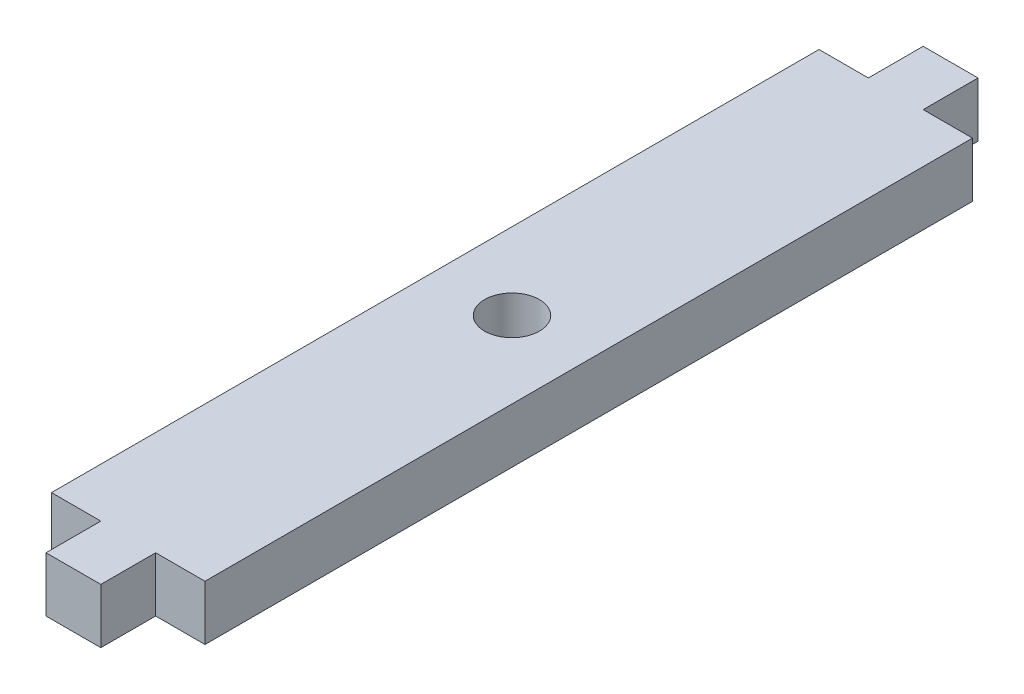
SolidWorks part; units mm, degrees
material "Pine"
ref_plane "Front Plane" through (0, 0, 0) normal (0, 0, 1) x (1, 0, 0)
ref_plane "Top Plane" through (0, 0, 0) normal (0, 1, 0) x (1, 0, 0)
ref_plane "Right Plane" through (0, 0, 0) normal (1, 0, 0) x (0, 0, -1)
sketch "Sketch1" plane through (0, 0, 0) normal (0, 1, 0) x (1, 0, 0)
  line L0 (0, 0) -> (0, 17.78)
  line L1 (0, 17.78) -> (-5.715, 17.78)
  line L2 (-5.715, 17.78) -> (-5.715, 24.13)
  line L3 (-5.715, 24.13) -> (-12.065, 24.13)
  line L4 (-12.065, 24.13) -> (-12.065, 17.78)
  line L5 (-12.065, 17.78) -> (-17.78, 17.78)
  line L6 (-17.78, 17.78) -> (-17.78, 0)
  line L12 (-17.78, -53.34) -> (-17.78, -71.12)
  line L14 (0, -71.12) -> (0, -53.34)
  line L18 (-17.78, -71.12) -> (-12.065, -71.12)
  line L19 (-12.065, -71.12) -> (-12.065, -77.47)
  line L20 (-12.065, -77.47) -> (-5.715, -77.47)
  line L21 (-5.715, -77.47) -> (-5.715, -71.12)
  line L22 (-5.715, -71.12) -> (0, -71.12)
  line L24 (-17.78, 0) -> (-17.78, -53.34)
  line L25 (0, 0) -> (0, -53.34)
  line L26 (-17.78, -26.67) -> (0, -26.67) construction
  circle A2 centre (-8.89, -26.67) radius 3.175
  dimension "D5" = 5.715
  dimension "D9" = 6.35
  dimension "D1" = 17.78
  dimension "D2" = 17.78
  dimension "D3" = 6.35
  dimension "D4" = 6.35
  dimension "D6" = 17.78
  dimension "D7" = 53.34
  dimension "D8" = 17.78
  dimension "D10" = 6.35
  dimension "D12" = 6.35
  dimension "D14" = 5.715
extrude "Boss-Extrude1" add sketch "Sketch1" along normal blind 6.35
